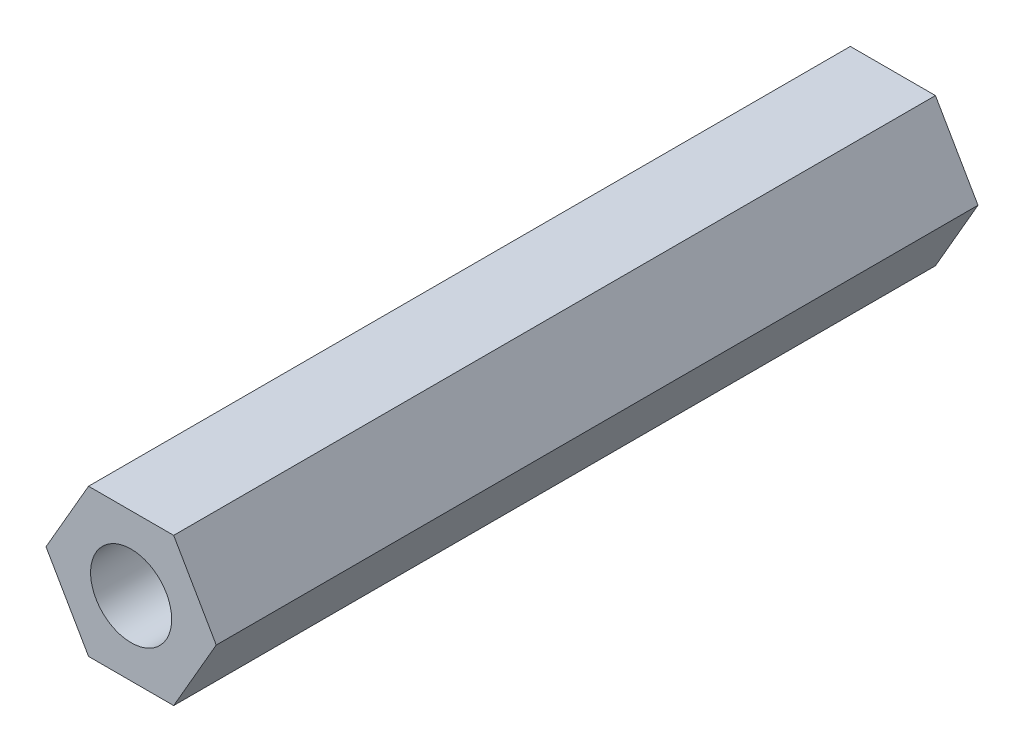
SolidWorks part; units mm, degrees
ref_plane "Front Plane" through (0, 0, 0) normal (0, 0, 1) x (1, 0, 0)
ref_plane "Top Plane" through (0, 0, 0) normal (0, 1, 0) x (1, 0, 0)
ref_plane "Right Plane" through (0, 0, 0) normal (1, 0, 0) x (0, 0, -1)
sketch "Sketch1" plane through (0, 0, 0) normal (0, 0, 1) x (1, 0, 0)
  line L1 (1.7321, 3) -> (-1.7321, 3)
  line L2 (-1.7321, 3) -> (-3.4641, 0)
  line L3 (-3.4641, 0) -> (-1.7321, -3)
  line L4 (-1.7321, -3) -> (1.7321, -3)
  line L5 (1.7321, -3) -> (3.4641, 0)
  line L6 (3.4641, 0) -> (1.7321, 3)
  circle A0 centre (0, 0) radius 3 construction
  circle A1 centre (0, 0) radius 1.65
  dimension "D2" = 3.3
  dimension "D1" = 6
extrude "Boss-Extrude1" add sketch "Sketch1" along normal blind 31
